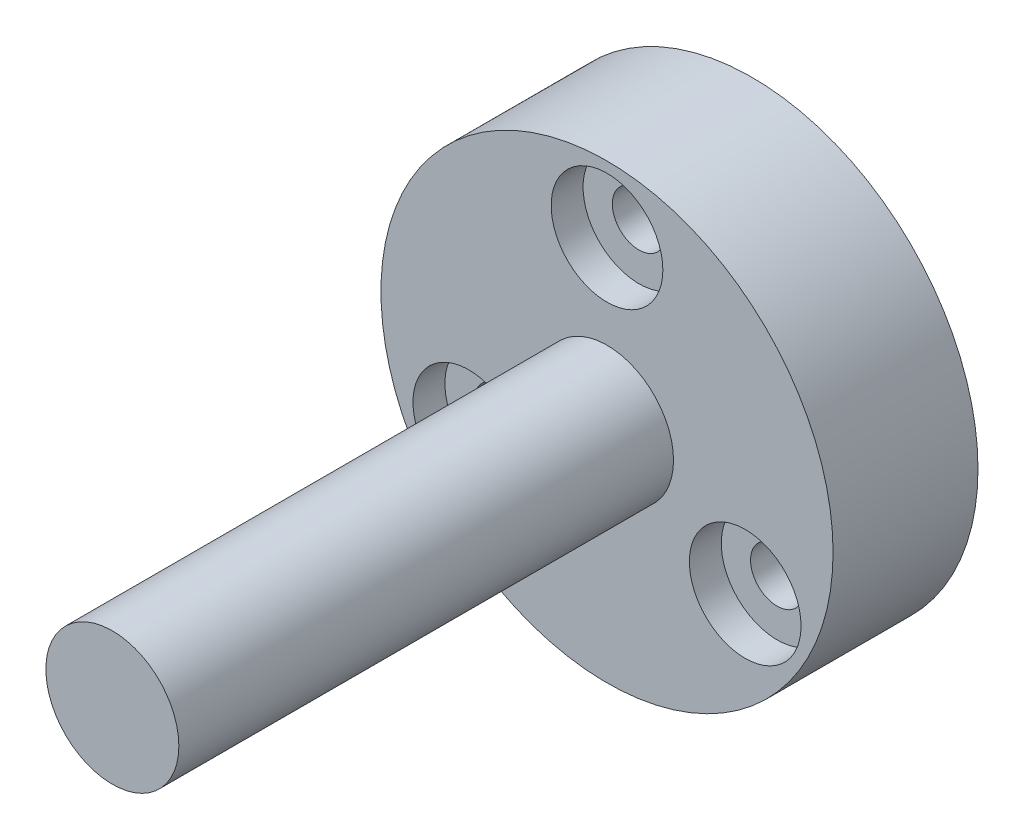
SolidWorks part; units mm, degrees
ref_plane "Front Plane" through (0, 0, 0) normal (0, 0, 1) x (1, 0, 0)
ref_plane "Top Plane" through (0, 0, 0) normal (0, 1, 0) x (1, 0, 0)
ref_plane "Right Plane" through (0, 0, 0) normal (1, 0, 0) x (0, 0, -1)
sketch "Sketch1" plane through (0, 0, 0) normal (0, 0, 1) x (1, 0, 0)
  circle A0 centre (0, 0) radius 8.5
  dimension "D1" = 17
extrude "Boss-Extrude1" add sketch "Sketch1" along normal blind 5.45
sketch "Sketch2" plane through (0, 0, 5.45) normal (0, 0, 1) x (1, 0, 0)
  circle A1 centre (0, 6) radius 1
  circle A2 centre (5.1962, -3) radius 1
  circle A3 centre (-5.1962, -3) radius 1
  point P11 (0, 0)
  dimension "D2" = 2
  dimension "D3" = 3
extrude "Cut-Extrude1" cut sketch "Sketch2" against normal blind 5.45
sketch "Sketch3" plane through (0, 0, 5.45) normal (0, 0, 1) x (1, 0, 0)
  circle A0 centre (0, 0) radius 2.5
  dimension "D1" = 5
extrude "Boss-Extrude2" add sketch "Sketch3" along normal blind 18.6
ref_plane "Plane3" through (0, 0, 5.45) normal (0, 0, 1) x (1, 0, 0)
sketch "Sketch6" plane through (0, 0, 5.45) normal (0, 0, 1) x (1, 0, 0)
  circle A0 centre (5.1962, -3) radius 2.1
  circle A1 centre (0, 6) radius 2.1
  circle A2 centre (-5.1962, -3) radius 2.1
  dimension "D1" = 4.2
  dimension "D2" = 4.2
  dimension "D3" = 4.2
extrude "Cut-Extrude2" cut sketch "Sketch6" against normal blind 1.2
sketch "Sketch7" plane through (0, 0, 0) normal (0, 0, -1) x (-1, 0, 0)
  circle A0 centre (0, 0) radius 4.5
  dimension "D1" = 9
extrude "Cut-Extrude3" cut sketch "Sketch7" against normal blind 2
